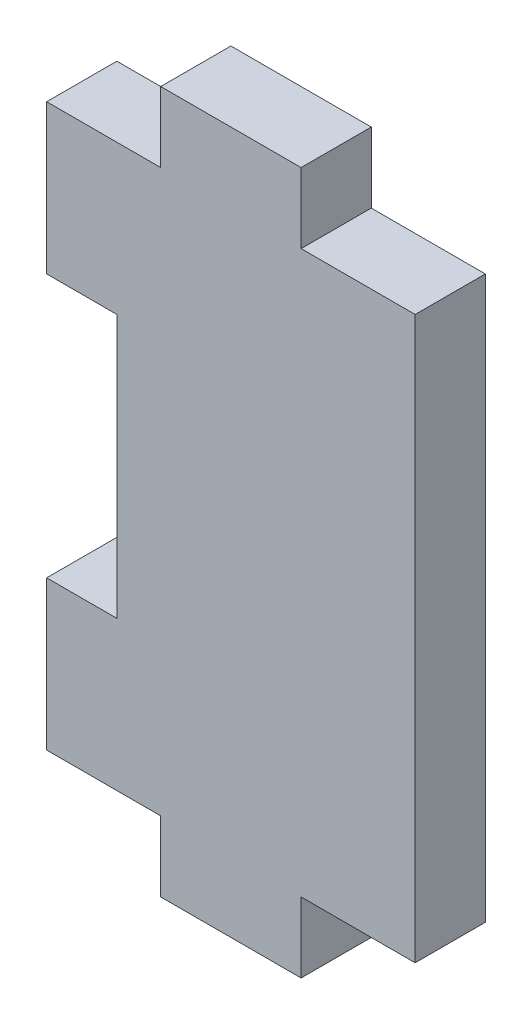
SolidWorks part; units mm, degrees
ref_plane "Спереди" through (0, 0, 0) normal (0, 0, 1) x (1, 0, 0)
ref_plane "Сверху" through (0, 0, 0) normal (0, 1, 0) x (1, 0, 0)
ref_plane "Справа" through (0, 0, 0) normal (1, 0, 0) x (0, 0, -1)
other "Configuration Table"
sketch "Эскиз1" plane through (0, 0, 0) normal (0, 0, 1) x (1, 0, 0)
  line L1 (0, 0) -> (21, 0)
  line L2 (0, 0) -> (0, 40)
  line L3 (0, 40) -> (21, 40)
  line L4 (21, 0) -> (21, 40)
  dimension "D1" = 21
  dimension "D2" = 40
extrude "Бобышка-Вытянуть1" add sketch "Эскиз1" along normal blind 4
sketch "Эскиз2" plane through (0, 0, 4) normal (0, 0, 1) x (1, 0, 0)
  line L0 (10.5, 40) -> (10.5, 0) construction
  line L1 (21, 40) -> (0, 40) construction
  line L2 (0, 0) -> (21, 0) construction
  line L3 (0, 20) -> (21, 20) construction
  line L4 (0, 40) -> (0, 0) construction
  line L5 (21, 0) -> (21, 40) construction
  line L6 (21, 36) -> (21, 40)
  line L7 (6.5, 36) -> (0, 36)
  line L8 (6.5, 36) -> (6.5, 40)
  line L9 (6.5, 40) -> (0, 40)
  line L10 (0, 36) -> (0, 40)
  line L11 (14.5, 40) -> (21, 40)
  line L12 (14.5, 36) -> (14.5, 40)
  line L13 (14.5, 36) -> (21, 36)
  line L14 (14.5, 4) -> (21, 4)
  line L15 (14.5, 4) -> (14.5, 0)
  line L16 (14.5, 0) -> (21, 0)
  line L17 (0, 4) -> (0, 0)
  line L18 (6.5, 0) -> (0, 0)
  line L19 (6.5, 4) -> (6.5, 0)
  line L20 (6.5, 4) -> (0, 4)
  line L21 (21, 4) -> (21, 0)
  line L22 (4, 27.5) -> (4, 12.5)
  line L23 (4, 27.5) -> (0, 27.5)
  line L24 (4, 12.5) -> (0, 12.5)
  line L25 (0, 27.5) -> (0, 12.5)
  point P33 (4, 20)
  dimension "D1" = 6.5
  dimension "D2" = 4
  dimension "D3" = 15
  dimension "D4" = 4
extrude "Вырез-Вытянуть1" cut sketch "Эскиз2" against normal blind 4
